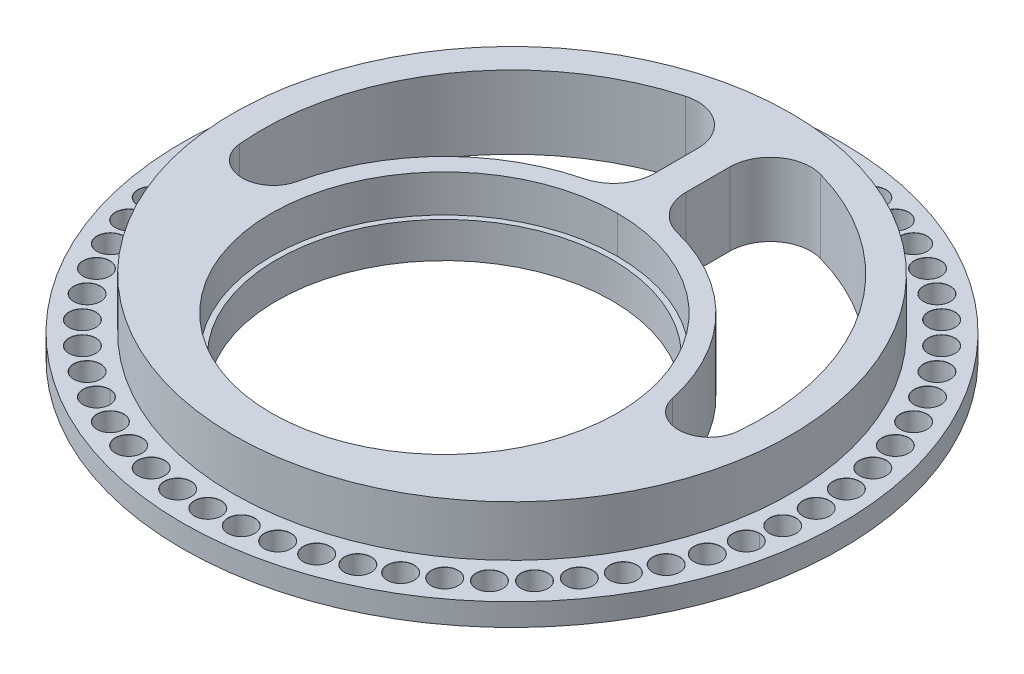
SolidWorks part; units mm, degrees
material "6061-T6 (SS)"
ref_plane "X-Y Datum" through (0, 0, 0) normal (0, 0, 1) x (1, 0, 0)
ref_plane "X-Z Datum" through (0, 0, 0) normal (0, 1, 0) x (1, 0, 0)
ref_plane "Y-Z Datum" through (0, 0, 0) normal (1, 0, 0) x (0, 0, -1)
sketch "Sketch1" plane through (0, 0, 0) normal (0, 1, 0) x (1, 0, 0)
  line L0 (0, 0) -> (0, -12.7) construction
  line L1 (0, -43.0151) -> (0, 43.0151) construction
  line L2 (0, 52.3875) -> (0, 61.9125) construction
  circle A0 centre (0, -12.7) radius 30.988
  circle A1 centre (0, 0) radius 52.3875 construction
  circle A2 centre (0, 0) radius 61.9125
  circle A3 centre (0, 0) radius 57.15 construction
  point P12 (0, 57.15)
  dimension "D2" = 61.976
  dimension "D3" = 104.775
  dimension "D4" = 123.825
  dimension "D5" = 114.3
  dimension "D1" = 12.7
extrude "Slotted-Body Extrude" add sketch "Sketch1" along normal blind 4.191
sketch "Sketch5" plane through (0, 4.191, 0) normal (0, 1, 0) x (1, 0, 0)
  circle A0 centre (0, 0) radius 52.3875 construction
  circle A1 centre (0, 0) radius 52.3875
extrude "Boss-Extrude3" add sketch "Sketch5" along normal blind 9.525
sketch "Sketch6" plane through (0, 0, 0) normal (0, -1, 0) x (1, 0, 0)
  line L0 (0, -79.2756) -> (0, 0) construction
  line L2 (3.014, -37.9067) -> (3.014, -29.6741)
  line L4 (-3.014, -37.9067) -> (-3.014, -29.6741)
  circle A0 centre (0, 12.7) radius 30.988 construction
  circle A1 centre (0, 12.7) radius 30.988 construction
  circle A2 centre (0, 12.7) radius 32.512
  arc A9 (-35.2562, 5.0907) -> (-8.7792, -22.2832) centre (0, 12.7) ccw
  arc A10 (-46.783, 4.406) -> (-12.6921, -45.2435) centre (0, 0) ccw
  arc A11 (-46.783, 4.406) -> (-35.2562, 5.0907) centre (-40.9667, 3.8583) cw
  arc A19 (-3.014, -29.6741) -> (-8.7792, -22.2832) centre (-10.634, -29.6741) ccw
  arc A20 (-3.014, -37.9067) -> (-12.6921, -45.2435) centre (-10.634, -37.9067) cw
  circle A21 centre (0, 0) radius 61.9125 construction
  arc A27 (46.783, 4.406) -> (35.2562, 5.0907) centre (40.9667, 3.8583) ccw
  arc A28 (46.783, 4.406) -> (12.6921, -45.2435) centre (0, 0) cw
  arc A29 (3.014, -37.9067) -> (12.6921, -45.2435) centre (10.634, -37.9067) ccw
  arc A30 (3.014, -29.6741) -> (8.7792, -22.2832) centre (10.634, -29.6741) cw
  arc A31 (35.2562, 5.0907) -> (8.7792, -22.2832) centre (0, 12.7) cw
  point P30 (0, 0)
  point P31 (-3.014, -23.2419)
  point P32 (0, 0)
  point P36 (-3.014, -46.8932)
  dimension "D1" = 65.024
  dimension "D2" = 7.62
  dimension "D3" = 5.842
  dimension "D4" = 46.99
  dimension "D5" = 7.62
  dimension "D6" = 36.068
  dimension "D8" = 8.2326
extrude "Cut-Extrude5" cut sketch "Sketch6" against normal through all
sketch "Sketch8" plane through (0, 0, 0) normal (0, -1, 0) x (1, 0, 0)
  circle A0 centre (0, 12.7) radius 32.512 construction
  circle A1 centre (0, 12.7) radius 32.512
  circle A2 centre (0, 12.7) radius 31.496
  dimension "D1" = 62.992
extrude "Boss-Extrude4" add sketch "Sketch8" against normal blind 6.7 separate body
hole_wizard "Ø5.0mm Dowel Hole1" positions "Sketch9" profile "Sketch10" hole size "Ø5.0" standard "ANSI Metric" end condition through all
sketch "Sketch9" plane through (0, 4.191, 0) normal (0, 1, 0) x (1, 0, 0)
  point P0 (0, 57.15)
sketch "Sketch10" plane through (0, 4.191, -57.15) normal (1, 0, 0) x (0, 0, 1)
  line L0 (0, 0) -> (0, 4.191)
  line L1 (0, 4.191) -> (2.5, 4.191)
  line L2 (2.5, 4.191) -> (2.5, 0.025)
  line L3 (2.5, 0.025) -> (2.525, 0)
  line L5 (2.525, 0) -> (0, 0)
  line L6 (-2.5, 0.025) -> (-2.525, 0) construction
  line L11 (0, -6.35) -> (0, 107.95) construction
  dimension "Thru Hole Dia." = 5
  dimension "Thru Hole Depth" = 4.191
  dimension "Near C'Sink Dia." = 5.05
  dimension "Near C'Sink Angle" = 90
pattern_circular "CirPattern1" count 60 over 360 about axis through (0, 0, 0) along (0, 1, 0) of "Ø5.0mm Dowel Hole1"
ref_point "Point1"
ref_plane "Plane1" through (0, 0, 0) normal (1, 0, 0) x (0, 0, -1)
split line "Split Line1"
ref_point "Point2"
ref_point "Point3"
ref_point "Point4"
ref_point "Point5"
split line "Split Line2"
split line "Split Line3"
ref_plane "Plane2" through (-42.4707, 0, 0) normal (-1, 0, 0) x (0, 0, 1)
ref_plane "Plane3" through (55.9011, 0, 0) normal (-1, 0, 0) x (0, 0, 1)
split line "Split Line4"
split line "Split Line5"
